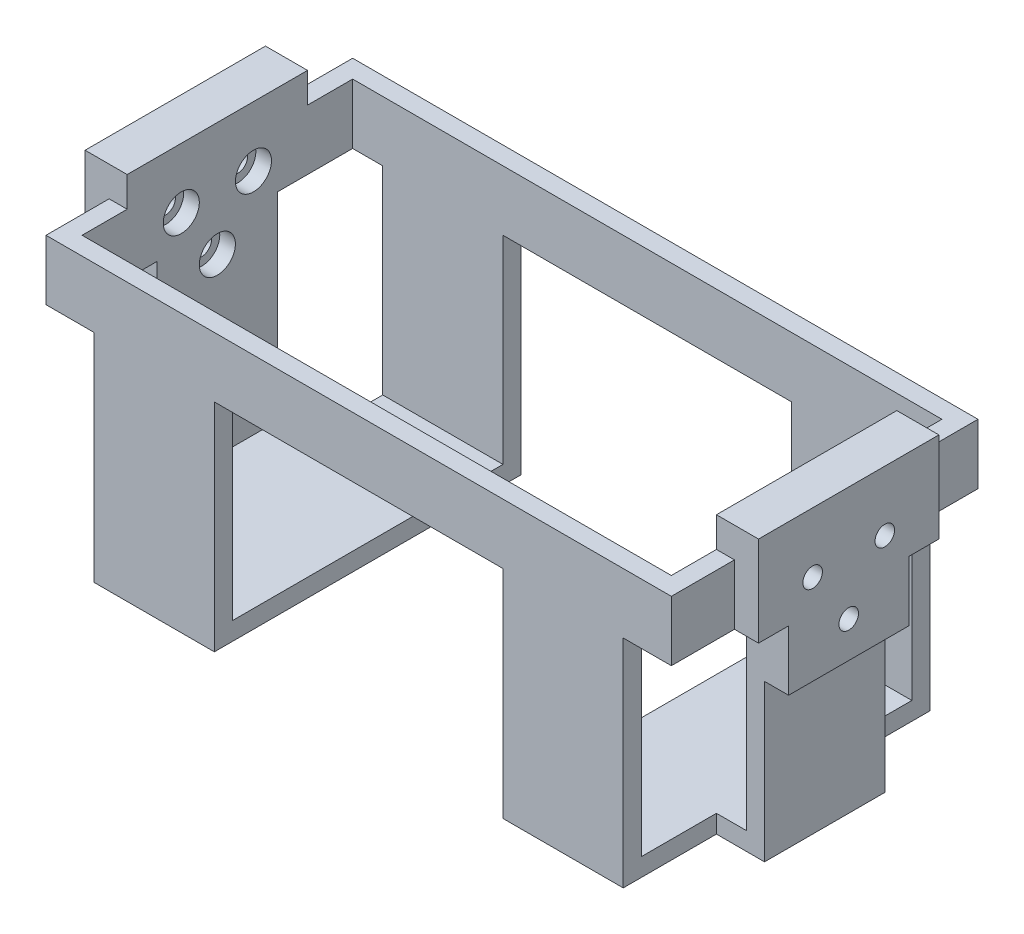
SolidWorks part; units mm, degrees
ref_plane "Спереди" through (0, 0, 0) normal (0, 0, 1) x (1, 0, 0)
ref_plane "Сверху" through (0, 0, 0) normal (0, 1, 0) x (1, 0, 0)
ref_plane "Справа" through (0, 0, 0) normal (1, 0, 0) x (0, 0, -1)
sketch "Эскиз1" plane through (0, 0, 0) normal (0, 1, 0) x (1, 0, 0)
  line L11 (0, 59.2084) -> (0, -58.6713) construction
  line L15 (24, 25.5) -> (44, 25.5)
  line L24 (44, 25.5) -> (44, 10)
  line L25 (44, 10) -> (52, 10)
  line L26 (52, 10) -> (52, -10)
  line L27 (52, -10) -> (44, -10)
  line L28 (44, -10) -> (44, -25.5)
  line L29 (44, -25.5) -> (24, -25.5)
  line L30 (24, -25.5) -> (24, 25.5)
  line L31 (24, 0) -> (-24, 0) construction
  line L32 (24, 22.5) -> (44, 22.5) construction
  line L33 (24, -22.5) -> (44, -22.5) construction
  line L34 (-24, -22.5) -> (-44, -22.5) construction
  line L35 (-24, 22.5) -> (-44, 22.5) construction
  line L36 (-24, -25.5) -> (-24, 25.5)
  line L37 (-44, -25.5) -> (-24, -25.5)
  line L38 (-44, -10) -> (-44, -25.5)
  line L39 (-52, -10) -> (-44, -10)
  line L40 (-52, 10) -> (-52, -10)
  line L41 (-44, 10) -> (-52, 10)
  line L42 (-44, 25.5) -> (-44, 10)
  line L43 (-24, 25.5) -> (-44, 25.5)
  dimension "D10" = 51
  dimension "D11" = 20
  dimension "D12" = 24
  dimension "D13" = 20
  dimension "D14" = 3
  dimension "D15" = 3
  dimension "D16" = 8
  dimension "D17" = 104
extrude "Бобышка-Вытянуть1" add sketch "Эскиз1" along normal blind 3
sketch "Эскиз2" plane through (0, 3, 0) normal (0, 1, 0) x (1, 0, 0)
  line L0 (-61.3503, 0) -> (73.9162, 0) construction
  line L1 (44, 10) -> (44, 25.5) construction
  line L2 (24, 25.5) -> (44, 25.5)
  line L3 (24, 25.5) -> (24, 22.5)
  line L4 (24, 22.5) -> (44, 22.5)
  line L5 (44, 25.5) -> (44, 22.5)
  line L6 (0, 35.6791) -> (0, -41.0709) construction
  line L7 (52, 10) -> (44, 10) construction
  line L8 (49, 10) -> (52, 10)
  line L9 (49, 10) -> (49, -10)
  line L10 (49, -10) -> (52, -10)
  line L11 (52, 10) -> (52, -10)
  line L12 (44, -25.5) -> (44, -22.5)
  line L13 (24, -22.5) -> (44, -22.5)
  line L14 (24, -25.5) -> (24, -22.5)
  line L15 (24, -25.5) -> (44, -25.5)
  line L16 (61.3503, 0) -> (-73.9162, 0) construction
  line L17 (-24, -25.5) -> (-44, -25.5)
  line L18 (-24, -25.5) -> (-24, -22.5)
  line L19 (-24, -22.5) -> (-44, -22.5)
  line L20 (-44, -25.5) -> (-44, -22.5)
  line L21 (-52, 10) -> (-52, -10)
  line L22 (-49, -10) -> (-52, -10)
  line L23 (-49, 10) -> (-49, -10)
  line L24 (-49, 10) -> (-52, 10)
  line L25 (-44, 25.5) -> (-44, 22.5)
  line L26 (-24, 22.5) -> (-44, 22.5)
  line L27 (-24, 25.5) -> (-24, 22.5)
  line L28 (-24, 25.5) -> (-44, 25.5)
  dimension "D1" = 3
extrude "Бобышка-Вытянуть2" add sketch "Эскиз2" along normal blind 43
sketch "Эскиз3" plane through (0, 46, 0) normal (0, 1, 0) x (1, 0, 0)
  line L0 (44, 25.5) -> (52, 25.5)
  line L1 (-24, 25.5) -> (24, 25.5)
  line L2 (-24, 25.5) -> (-24, 22.5)
  line L3 (-24, 22.5) -> (24, 22.5)
  line L4 (24, 25.5) -> (24, 22.5)
  line L5 (52, 25.5) -> (52, 10)
  line L6 (52, 10) -> (49, 10)
  line L7 (49, 10) -> (49, 22.5)
  line L8 (49, 22.5) -> (44, 22.5)
  line L9 (44, 22.5) -> (44, 25.5)
  line L10 (0, 35.4654) -> (0, -34.1197) construction
  line L11 (-58.6072, 0) -> (75.5319, 0) construction
  line L12 (-44, 22.5) -> (-44, 25.5)
  line L13 (-49, 22.5) -> (-44, 22.5)
  line L14 (-49, 10) -> (-49, 22.5)
  line L15 (-52, 10) -> (-49, 10)
  line L16 (-52, 25.5) -> (-52, 10)
  line L17 (-44, 25.5) -> (-52, 25.5)
  line L18 (58.6072, 0) -> (-75.5319, 0) construction
  line L19 (0, -35.4654) -> (0, 34.1197) construction
  line L20 (-44, -25.5) -> (-52, -25.5)
  line L21 (-52, -25.5) -> (-52, -10)
  line L22 (-52, -10) -> (-49, -10)
  line L23 (-49, -10) -> (-49, -22.5)
  line L24 (-49, -22.5) -> (-44, -22.5)
  line L25 (-44, -22.5) -> (-44, -25.5)
  line L26 (44, -22.5) -> (44, -25.5)
  line L27 (49, -22.5) -> (44, -22.5)
  line L28 (49, -10) -> (49, -22.5)
  line L29 (52, -10) -> (49, -10)
  line L30 (52, -25.5) -> (52, -10)
  line L31 (24, -25.5) -> (24, -22.5)
  line L32 (-24, -22.5) -> (24, -22.5)
  line L33 (-24, -25.5) -> (-24, -22.5)
  line L34 (-24, -25.5) -> (24, -25.5)
  line L35 (44, -25.5) -> (52, -25.5)
extrude "Бобышка-Вытянуть3" add sketch "Эскиз3" against normal blind 10
sketch "Эскиз4" plane through (-52, 0, 0) normal (-1, 0, 0) x (0, 0, 1)
  line L0 (-10, 36) -> (-10, 0) construction
  line L1 (-10, 26) -> (10, 26)
  line L2 (-10, 26) -> (-10, 36)
  line L3 (-15, 46) -> (15, 46)
  line L4 (10, 26) -> (10, 36)
  line L5 (-25.5, 46) -> (25.5, 46) construction
  line L11 (-10, 36) -> (-15, 36)
  line L12 (-15, 36) -> (-15, 46)
  line L14 (10, 36) -> (15, 36)
  line L16 (15, 36) -> (15, 46)
  line L18 (10, 36) -> (25.5, 36) construction
  line L19 (10, 36) -> (10, 0) construction
  dimension "D1" = 10
  dimension "D2" = 5
extrude "Бобышка-Вытянуть4" add sketch "Эскиз4" along normal blind 4
sketch "Эскиз5" plane through (-49, 0, 0) normal (1, 0, 0) x (0, 0, -1)
  line L1 (0, 46) -> (0, 3) construction
  line L3 (-25.5, 41) -> (22.5, 41) construction
  line L7 (-25.5, 46) -> (25.5, 46) construction
  line L8 (-25.5, 36) -> (-25.5, 46) construction
  circle A0 centre (-6, 41) radius 3
  circle A1 centre (0, 32) radius 3
  circle A2 centre (6, 41) radius 3
  dimension "D1" = 9
  dimension "D2" = 6
extrude "Вырез-Вытянуть1" cut sketch "Эскиз5" against normal blind 2.6
ref_point "Точка1"
ref_point "Точка2"
ref_point "Точка3"
sketch "Эскиз7" plane through (-51.6, 0, 0) normal (1, 0, 0) x (0, 0, -1)
  circle A0 centre (-6, 41) radius 1.625
  circle A1 centre (6, 41) radius 1.625
  circle A2 centre (0, 32) radius 1.625
  dimension "D1" = 3.25
extrude "Вырез-Вытянуть2" cut sketch "Эскиз7" against normal through all
ref_plane "Плоскость1" through (0, 0, 0) normal (1, 0, 0) x (0, 0, -1)
mirror "Зеркальное отражение2" about plane through (0, 0, 0) normal (1, 0, 0) of "Вырез-Вытянуть1", "Бобышка-Вытянуть4", "Вырез-Вытянуть2"
sketch "Эскиз8" plane through (0, 46, 0) normal (0, 1, 0) x (1, 0, 0)
  line L0 (-56, 15) -> (-56, -15)
  line L1 (-56, 15) -> (-49, 15)
  line L2 (-56, -15) -> (-49, -15)
  line L3 (-49, 15) -> (-49, -15)
  line L4 (56, 15) -> (56, -15)
  line L5 (56, 15) -> (49, 15)
  line L6 (56, -15) -> (49, -15)
  line L7 (49, 15) -> (49, -15)
  line L8 (49, 22.5) -> (49, -22.5) construction
  line L9 (-49, -10) -> (-49, 10) construction
extrude "Бобышка-Вытянуть5" add sketch "Эскиз8" along normal blind 5
